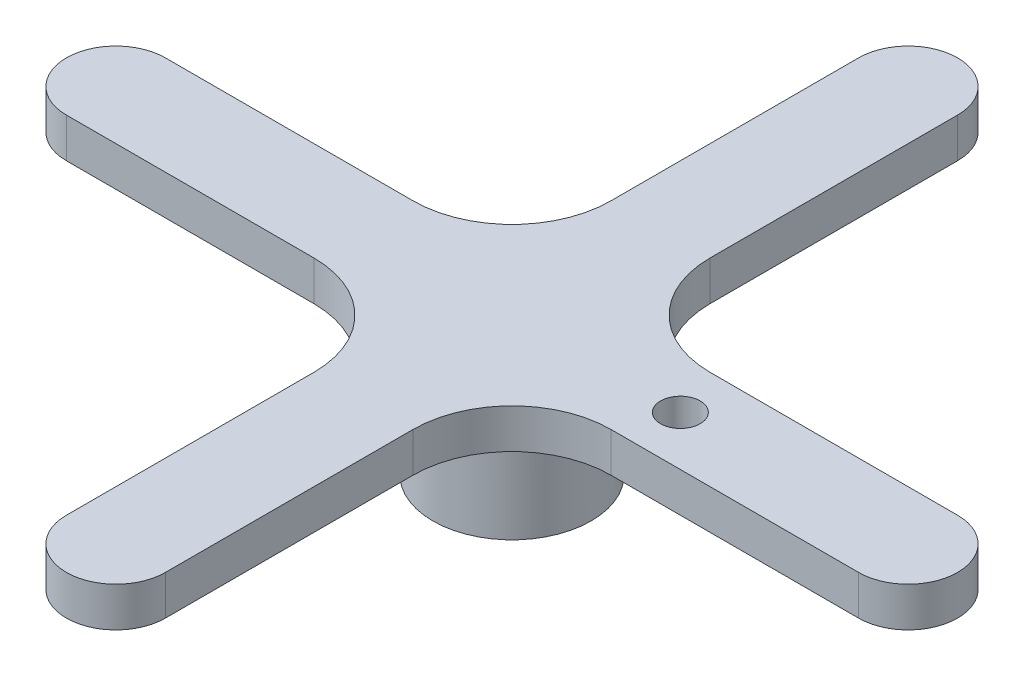
SolidWorks part; units mm, degrees
ref_plane "Front Plane" through (0, 0, 0) normal (0, 0, 1) x (1, 0, 0)
ref_plane "Top Plane" through (0, 0, 0) normal (0, 1, 0) x (1, 0, 0)
ref_plane "Right Plane" through (0, 0, 0) normal (1, 0, 0) x (0, 0, -1)
sketch "Sketch1" plane through (0, 0, 0) normal (0, 1, 0) x (1, 0, 0)
  line L2 (2.5, 20) -> (2.5, 7.5)
  line L4 (-2.5, 20) -> (-2.5, 7.5)
  line L7 (-20, 2.5) -> (-7.5, 2.5)
  line L9 (-20, -2.5) -> (-7.5, -2.5)
  line L14 (-2.5, -7.5) -> (-2.5, -20)
  line L16 (7.5, -2.5) -> (20, -2.5)
  line L18 (2.5, -7.5) -> (2.5, -20)
  line L19 (7.5, 2.5) -> (20, 2.5)
  arc A0 (-2.5, -7.5) -> (-7.5, -2.5) centre (-7.5, -7.5) ccw
  arc A1 (7.5, -2.5) -> (2.5, -7.5) centre (7.5, -7.5) ccw
  arc A2 (2.5, 7.5) -> (7.5, 2.5) centre (7.5, 7.5) ccw
  arc A3 (-7.5, 2.5) -> (-2.5, 7.5) centre (-7.5, 7.5) ccw
  arc A4 (-2.5, 20) -> (2.5, 20) centre (0, 20) cw
  arc A5 (20, 2.5) -> (20, -2.5) centre (20, 0) cw
  arc A6 (-2.5, -20) -> (2.5, -20) centre (0, -20) ccw
  arc A7 (-20, 2.5) -> (-20, -2.5) centre (-20, 0) ccw
  circle A8 centre (0, 0) radius 8.5 construction
  circle A9 centre (8.5, 0) radius 1
  circle A10 centre (0, -8.5) radius 1
  circle A11 centre (-8.5, 0) radius 1
  circle A12 centre (0, 8.5) radius 1
  point P0 (0, 0)
  point P6 (0, 0)
  point P20 (2.5, -2.5)
  point P41 (0, 0)
  dimension "D5" = 17
  dimension "D6" = 2
  dimension "D7" = 4
  dimension "D8" = 5
  dimension "D9" = 5
  dimension "D10" = 5
  dimension "D1" = 40
  dimension "D2" = 40
  dimension "D3" = 5
  dimension "D4" = 5
extrude "Boss-Extrude1" add sketch "Sketch1" along normal blind 2
sketch "Sketch2" plane through (0, 0, 0) normal (0, -1, 0) x (1, 0, 0)
  circle A0 centre (0, 0) radius 4
  circle A1 centre (0, 0) radius 2.95
  dimension "D1" = 8
  dimension "D2" = 5.9
extrude "Boss-Extrude2" add sketch "Sketch2" along normal blind 5
